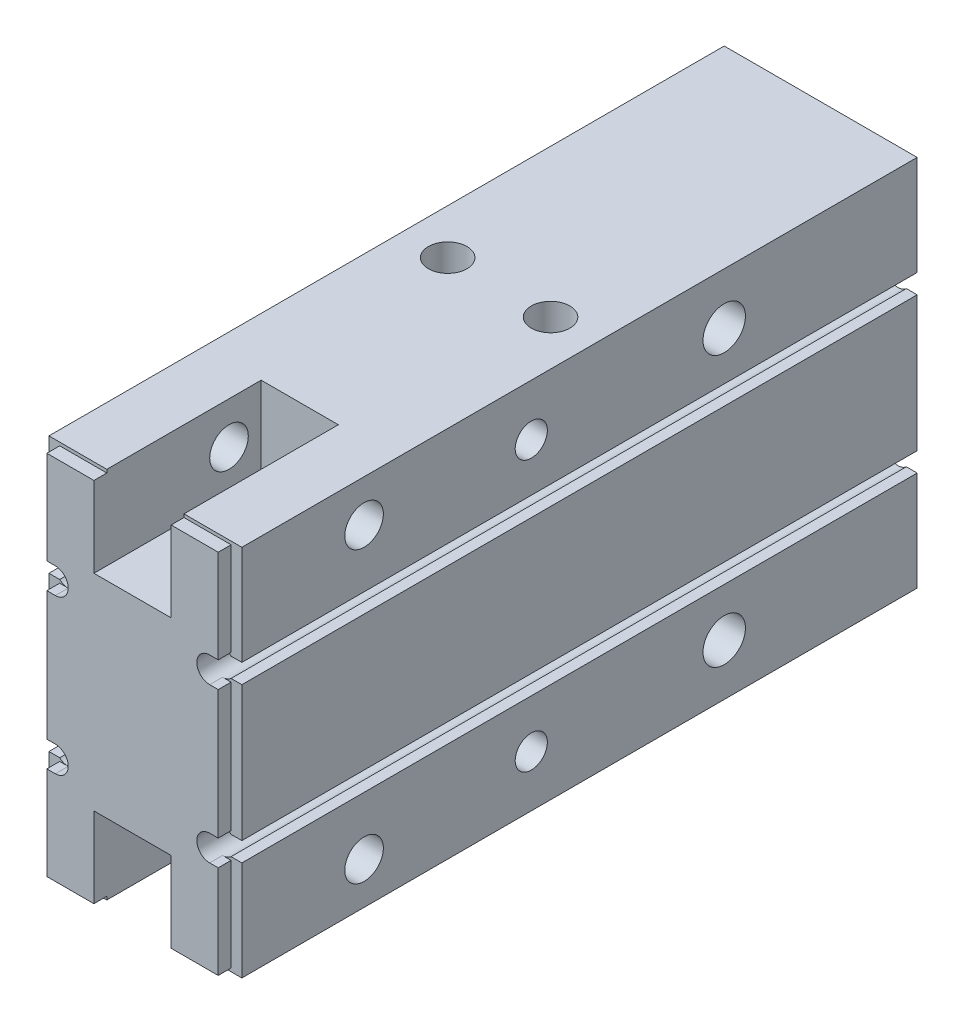
SolidWorks part; units mm, degrees
ref_plane "Top" through (0, 0, 0) normal (0, 0, 1) x (1, 0, 0)
ref_plane "Front" through (0, 0, 0) normal (0, 1, 0) x (1, 0, 0)
ref_plane "Right" through (0, 0, 0) normal (1, 0, 0) x (0, 0, -1)
sketch "Sketch1" plane through (0, 0, 0) normal (0, 0, 1) x (1, 0, 0)
  line L0 (-120, 0) -> (140, 0) construction
  line L1 (0, 110) -> (0, -100) construction
  line L2 (-15, 29) -> (15, 29)
  line L3 (15, 29) -> (15, 13.5)
  line L4 (-40, 12) -> (70, 12) construction
  line L5 (13.3229, 13.5) -> (15, 13.5)
  line L6 (13.3229, 10.5) -> (15, 10.5)
  line L7 (15, 10.5) -> (15, -10.5)
  line L8 (13.3229, -13.5) -> (15, -13.5)
  line L9 (13.3229, -10.5) -> (15, -10.5)
  line L10 (15, -29) -> (15, -13.5)
  line L11 (-15, -29) -> (15, -29)
  line L12 (-13.3229, -13.5) -> (-15, -13.5)
  line L13 (-13.3229, -10.5) -> (-15, -10.5)
  line L14 (-13.3229, 10.5) -> (-15, 10.5)
  line L15 (-13.3229, 13.5) -> (-15, 13.5)
  line L16 (-15, -29) -> (-15, -13.5)
  line L17 (-15, 10.5) -> (-15, -10.5)
  line L18 (-15, 29) -> (-15, 13.5)
  arc A0 (13.3229, 10.5) -> (13.3229, 13.5) centre (12, 12) cw
  arc A1 (13.3229, -10.5) -> (13.3229, -13.5) centre (12, -12) ccw
  arc A2 (-13.3229, -10.5) -> (-13.3229, -13.5) centre (-12, -12) cw
  arc A3 (-13.3229, 10.5) -> (-13.3229, 13.5) centre (-12, 12) ccw
  point P20 (15, 0)
  point P31 (0, -29)
  point P34 (0, 29)
  dimension "GROOVEDIAMETER" = 4
  dimension "WIDTH" = 30
  dimension "HEIGHT" = 58
  dimension "EDGETOGROOVE" = 3
  dimension "CENTERTOGROOVE" = 12
  dimension "ARCEDGES" = 3
extrude "Body" add sketch "Sketch1" along normal blind 105
sketch "Sketch4" plane through (15, 0, 0) normal (1, 0, 0) x (0, 0, -1)
  line L0 (0, 0) -> (-60, 0) construction
  circle A0 centre (-30, 21) radius 3.3
  circle A1 centre (-30, -21) radius 3.3
  dimension "THRUHOLEDIAMETER" = 6.6
  dimension "CENTERTOHOLE" = 21
  dimension "EDGETOHOLE" = 30
extrude "ThroughHoles" cut sketch "Sketch4" against normal through all
sketch "Sketch6" plane through (15, -52.9203, -22.0414) normal (1, 0, 0) x (0, 0, -1)
  line L0 (-10, 52.9203) -> (-90, 52.9203) construction
  point P0 (-57.0414, 64.9203)
  dimension "EDGETOHOLE" = 35
  dimension "CENTERTOHOLE" = 12
sketch "Sketch7" plane through (7.5, 12, 35) normal (0, 1, 0) x (0, 0, -1)
  line L0 (0, 0) -> (0, 6.9013)
  line L1 (0, 6.9013) -> (1.5, 6)
  line L2 (1.5, 6) -> (1.5, 0)
  line L4 (1.5, 0) -> (0, 0)
  line L6 (0, 6.9013) -> (-1.5, 6) construction
  line L7 (0, -4.2442) -> (0, 117.3081) construction
  dimension "Diameter" = 3
  dimension "Depth" = 6
  dimension "Drill Angle" = 118
hole_wizard "M3 x 0.5 #1(Size=10)" positions "Sketch6" profile "Sketch7" legacy
cosmetic thread "Cosmetic Thread1"
mirror "M3 x 0.5 #2(Size=10)" [suppressed] about plane through (0, 0, 0) normal (0, 1, 0)
mirror "M3 x 0.5 Other Side (Size-10)" [suppressed] about plane through (0, 0, 0) normal (1, 0, 0)
ref_plane "FingerPivotPlane" through (0, 0, 47.5) normal (0, 0, -1) x (-1, 0, 0)
sketch "Sketch10" plane through (15, 0, 0) normal (1, 0, 0) x (0, 0, -1)
  line L1 (0, 0) -> (-60, 0) construction
  circle A0 centre (-86, 22.5) radius 3
  circle A1 centre (-86, -22.5) radius 3
  dimension "PIVOTHOLEDIAMETER" = 6
  dimension "BETWEENPIVOTHOLES" = 45
  dimension "EDGETOPIVOTHOLES" = 86
extrude "FingerPivotHoles" cut sketch "Sketch10" against normal through all
sketch "Sketch13" plane through (-54.6295, -67.953, 0) normal (0, 0, -1) x (-1, 0, 0)
  line L0 (-54.6295, 67.953) -> (-54.6295, 41.1673) construction
  line L1 (-54.6295, 67.953) -> (-65.2953, 67.953) construction
  point P0 (-59.1295, 55.953)
  dimension "D1" = 12
  dimension "D2" = 4.5
sketch "Sketch14" plane through (4.5, -12, 0) normal (1, 0, 0) x (0, 1, 0)
  line L0 (0, 0) -> (0, 6.9013)
  line L1 (0, 6.9013) -> (1.5, 6)
  line L2 (1.5, 6) -> (1.5, 0)
  line L4 (1.5, 0) -> (0, 0)
  line L6 (0, 6.9013) -> (-1.5, 6) construction
  line L7 (0, -4.2442) -> (0, 117.3081) construction
  dimension "Diameter" = 3
  dimension "Depth" = 6
  dimension "Drill Angle" = 118
hole_wizard "M3 x 0.5 BackHole1(Size=10)" positions "Sketch13" profile "Sketch14" legacy
cosmetic thread "Cosmetic Thread4"
sketch "Sketch15" plane through (-57.0024, -57.4961, 0) normal (0, 0, -1) x (-1, 0, 0)
  line L0 (-57.0024, 57.4961) -> (-47.2287, 57.4961) construction
  line L1 (-57.0024, 57.4961) -> (-57.0024, 74.8688) construction
  point P0 (-52.5024, 69.4961)
  dimension "D1" = 4.5
  dimension "D2" = 12
sketch "Sketch16" plane through (-4.5, 12, 0) normal (1, 0, 0) x (0, 1, 0)
  line L0 (0, 0) -> (0, 7.8026)
  line L1 (0, 7.8026) -> (3, 6)
  line L2 (3, 6) -> (3, 0)
  line L4 (3, 0) -> (0, 0)
  line L6 (0, 7.8026) -> (-3, 6) construction
  line L7 (0, -4.2442) -> (0, 117.3081) construction
  dimension "Diameter" = 6
  dimension "Depth" = 6
  dimension "Drill Angle" = 118
hole_wizard "M3 x 0.5 BackHole2(Size=10)" positions "Sketch15" profile "Sketch16" legacy
cosmetic thread "Cosmetic Thread5"
sketch "Sketch17" plane through (0, 0, 0) normal (0, 0, -1) x (-1, 0, 0)
  line L0 (-2, -22.5) -> (-2, -23.5)
  line L1 (0, 0) -> (0, -20) construction
  line L2 (2, -22.5) -> (2, -23.5)
  line L3 (-1.6896, -23) -> (1.7545, -23) construction
  arc A0 (-2, -22.5) -> (2, -22.5) centre (0, -22.5) cw
  arc A1 (-2, -23.5) -> (2, -23.5) centre (0, -23.5) ccw
  point P11 (2, -23)
  point P13 (-2, -23)
  dimension "WIDTH" = 4
  dimension "CENTERTOPINHOLE" = 23
  dimension "ARCTOARC" = 5
extrude "PositioningPinHole" cut sketch "Sketch17" against normal blind 4
sketch "Sketch19" plane through (15, -50.4003, -22.2138) normal (1, 0, 0) x (0, 0, -1)
  line L0 (-22.2138, 50.4003) -> (-91.423, 50.4003) construction
  point P0 (-51.1745, 65.1278)
  dimension "D1" = 14.7275
  dimension "D2" = 28.9607
sketch "Sketch20" plane through (10, 15, 41) normal (0, 1, 0) x (0, 0, -1)
  line L0 (0, 0) -> (0, 9.8026)
  line L1 (0, 9.8026) -> (3, 8)
  line L2 (3, 8) -> (3, 0)
  line L4 (3, 0) -> (0, 0)
  line L6 (0, 9.8026) -> (-3, 8) construction
  line L7 (0, -4.2442) -> (0, 117.3081) construction
  dimension "Diameter" = 6
  dimension "Depth" = 8
  dimension "Drill Angle" = 118
hole_wizard "M4 x 0.7 #1(Size=16)" positions "Sketch19" profile "Sketch20" legacy
cosmetic thread "Cosmetic Thread6"
mirror "M4 x 0.7 #2(Size=16)" [suppressed] about plane through (0, 0, 0) normal (0, 1, 0)
sketch "Sketch21" plane through (-45.6216, -81.2682, 0) normal (0, 0, -1) x (-1, 0, 0)
  point P0 (-51.1745, 65.1278)
  dimension "D1" = 16.1404
  dimension "D2" = 5.5529
sketch "Sketch22" plane through (6, -15, 0) normal (1, 0, 0) x (0, 1, 0)
  line L0 (0, 0) -> (0, 9.8026)
  line L1 (0, 9.8026) -> (3, 8)
  line L2 (3, 8) -> (3, 0)
  line L4 (3, 0) -> (0, 0)
  line L6 (0, 9.8026) -> (-3, 8) construction
  line L7 (0, -4.2442) -> (0, 117.3081) construction
  dimension "Diameter" = 6
  dimension "Depth" = 8
  dimension "Drill Angle" = 118
mirror "M4 x 0.7 Other Side(Size=16)" [suppressed] about plane through (0, 0, 0) normal (1, 0, 0)
hole_wizard "M4 x 0.7 BackHole1(Size=16)" positions "Sketch21" profile "Sketch22" legacy
cosmetic thread "Cosmetic Thread7"
sketch "Sketch23" plane through (-57.3197, -49.0614, 0) normal (0, 0, -1) x (-1, 0, 0)
  point P0 (-51.1745, 65.1278)
  dimension "D1" = 6.1452
  dimension "D2" = 16.0664
sketch "Sketch24" plane through (-6, 15, 0) normal (1, 0, 0) x (0, 1, 0)
  line L0 (0, 0) -> (0, 9.8026)
  line L1 (0, 9.8026) -> (3, 8)
  line L2 (3, 8) -> (3, 0)
  line L4 (3, 0) -> (0, 0)
  line L6 (0, 9.8026) -> (-3, 8) construction
  line L7 (0, -4.2442) -> (0, 117.3081) construction
  dimension "Diameter" = 6
  dimension "Depth" = 8
  dimension "Drill Angle" = 118
hole_wizard "M4 x 0.7 BackHole2(Size=16)" positions "Sketch23" profile "Sketch24" legacy
cosmetic thread "Cosmetic Thread8"
sketch "Sketch26" plane through (15, -46.961, 3.7549) normal (1, 0, 0) x (0, 0, -1)
  point P0 (-51.1745, 65.1278)
  dimension "D1" = 18.1667
  dimension "D2" = 54.9295
sketch "Sketch27" plane through (13, 18, 50) normal (0, 1, 0) x (0, 0, -1)
  line L0 (0, 0) -> (0, 11.8026)
  line L1 (0, 11.8026) -> (3, 10)
  line L2 (3, 10) -> (3, 0)
  line L4 (3, 0) -> (0, 0)
  line L6 (0, 11.8026) -> (-3, 10) construction
  line L7 (0, -4.2442) -> (0, 117.3081) construction
  dimension "Diameter" = 6
  dimension "Depth" = 10
  dimension "Drill Angle" = 118
hole_wizard "M5 x 0.8 #1(Size=20)" positions "Sketch26" profile "Sketch27" legacy
cosmetic thread "Cosmetic Thread9"
mirror "M5 x 0.8 #2(Size=20)" [suppressed] about plane through (0, 0, 0) normal (0, 1, 0)
sketch "Sketch31" plane through (-41.9158, -85.0481, 0) normal (0, 0, -1) x (-1, 0, 0)
  point P0 (-51.1745, 65.1278)
  dimension "D1" = 19.9203
  dimension "D2" = 9.2587
sketch "Sketch32" plane through (8, -19, 0) normal (1, 0, 0) x (0, 1, 0)
  line L0 (0, 0) -> (0, 11.8026)
  line L1 (0, 11.8026) -> (3, 10)
  line L2 (3, 10) -> (3, 0)
  line L4 (3, 0) -> (0, 0)
  line L6 (0, 11.8026) -> (-3, 10) construction
  line L7 (0, -4.2442) -> (0, 117.3081) construction
  dimension "Diameter" = 6
  dimension "Depth" = 10
  dimension "Drill Angle" = 118
mirror "M5 x 0.8 Other Side(Size=20)" [suppressed] about plane through (0, 0, 0) normal (1, 0, 0)
hole_wizard "M5 x 0.8 BackHole1(Size=20)" positions "Sketch31" profile "Sketch32" legacy
cosmetic thread "Cosmetic Thread11"
sketch "Sketch28" plane through (-58.7499, -46.5168, 0) normal (0, 0, -1) x (-1, 0, 0)
  point P0 (-51.1745, 65.1278)
  dimension "D1" = 7.5753
  dimension "D2" = 18.611
sketch "Sketch29" plane through (-8, 19, 0) normal (1, 0, 0) x (0, 1, 0)
  line L0 (0, 0) -> (0, 9.8026)
  line L1 (0, 9.8026) -> (3, 8)
  line L2 (3, 8) -> (3, 0)
  line L4 (3, 0) -> (0, 0)
  line L6 (0, 9.8026) -> (-3, 8) construction
  line L7 (0, -4.2442) -> (0, 117.3081) construction
  dimension "Diameter" = 6
  dimension "Depth" = 8
  dimension "Drill Angle" = 118
hole_wizard "M5 x 0.8 BackHole2(Size=20)" positions "Sketch28" profile "Sketch29" legacy
cosmetic thread "Cosmetic Thread10"
sketch "Sketch34" plane through (15, -42.1788, 12.8) normal (1, 0, 0) x (0, 0, -1)
  point P0 (-47.2, 63.1788)
  dimension "D1" = 60
  dimension "D2" = 21
sketch "Sketch35" plane through (15, 21, 60) normal (0, 1, 0) x (0, 0, -1)
  line L0 (0, 0) -> (0, 13.5022)
  line L1 (0, 13.5022) -> (2.5, 12)
  line L2 (2.5, 12) -> (2.5, 0)
  line L4 (2.5, 0) -> (0, 0)
  line L6 (0, 13.5022) -> (-2.5, 12) construction
  line L7 (0, -4.2442) -> (0, 117.3081) construction
  dimension "Diameter" = 5
  dimension "Depth" = 12
  dimension "Drill Angle" = 118
hole_wizard "M6 x 1.0 #1(Size=25)" positions "Sketch34" profile "Sketch35" legacy
cosmetic thread "Cosmetic Thread12"
mirror "M6 x 1.0 #2(Size=25)" about plane through (0, 0, 0) normal (0, 1, 0) of "M6 x 1.0 #1(Size=25)"
sketch "Sketch36" plane through (-60.7376, -41.4426, 0) normal (0, 0, -1) x (-1, 0, 0)
  point P0 (-51.7376, 64.4426)
  dimension "D1" = 9
  dimension "D2" = 23
sketch "Sketch37" plane through (-9, 23, 0) normal (1, 0, 0) x (0, 1, 0)
  line L0 (0, 0) -> (0, 13.8026)
  line L1 (0, 13.8026) -> (3, 12)
  line L2 (3, 12) -> (3, 0)
  line L4 (3, 0) -> (0, 0)
  line L6 (0, 13.8026) -> (-3, 12) construction
  line L7 (0, -4.2442) -> (0, 117.3081) construction
  dimension "Diameter" = 6
  dimension "Depth" = 12
  dimension "Drill Angle" = 118
mirror "M6 x 1.0 Other Side(Size=25)" about plane through (0, 0, 0) normal (1, 0, 0) of "M6 x 1.0 #2(Size=25)", "M6 x 1.0 #1(Size=25)"
hole_wizard "M6 x 1.0 BackHole1(Size=25)" positions "Sketch36" profile "Sketch37" legacy
cosmetic thread "Cosmetic Thread13"
sketch "Sketch38" plane through (-41.9451, -86.5891, 0) normal (0, 0, -1) x (-1, 0, 0)
  point P0 (-50.9451, 63.5891)
  dimension "D1" = 23
  dimension "D2" = 9
sketch "Sketch39" plane through (9, -23, 0) normal (1, 0, 0) x (0, 1, 0)
  line L0 (0, 0) -> (0, 13.8026)
  line L1 (0, 13.8026) -> (3, 12)
  line L2 (3, 12) -> (3, 0)
  line L4 (3, 0) -> (0, 0)
  line L6 (0, 13.8026) -> (-3, 12) construction
  line L7 (0, -4.2442) -> (0, 117.3081) construction
  dimension "Diameter" = 6
  dimension "Depth" = 12
  dimension "Drill Angle" = 118
hole_wizard "M6 x 1.0 BackHole2(Size=25)" positions "Sketch38" profile "Sketch39" legacy
cosmetic thread "Cosmetic Thread14"
sketch "Sketch45" plane through (50.2848, -29, -56.2575) normal (0, -1, 0) x (1, 0, 0)
  line L0 (-50.2848, 56.2575) -> (-50.2848, 115.8439) construction
  line L1 (-50.2848, 60.2575) -> (-50.2848, 56.2575) construction
  point P0 (-57.2848, 64.2575)
  dimension "CENTERTOPORT" = 7
  dimension "EDGETOPORT" = 8
sketch "Sketch46" plane through (-7, -29, 8) normal (1, 0, 0) x (0, 0, -1)
  line L0 (0, 0) -> (0, 6.5022)
  line L1 (0, 6.5022) -> (2.5, 5)
  line L2 (2.5, 5) -> (2.5, 0)
  line L4 (2.5, 0) -> (0, 0)
  line L6 (0, 6.5022) -> (-2.5, 5) construction
  line L7 (0, -4.2442) -> (0, 117.3081) construction
  dimension "Diameter" = 5
  dimension "Depth" = 5
  dimension "Drill Angle" = 118
hole_wizard "M5 x 0.8 Port #1" positions "Sketch45" profile "Sketch46" legacy
cosmetic thread "Cosmetic Thread15"
sketch "Sketch47" plane through (54.7336, -29, -22.3356) normal (0, -1, 0) x (1, 0, 0)
  line L0 (-54.7336, 22.3356) -> (-54.7336, 82.3668) construction
  line L1 (-54.7336, 26.3356) -> (-54.7336, 22.3356) construction
  point P0 (-47.7336, 72.3356)
  dimension "PORTTOPORT" = 42
  dimension "CENTERTOPORT" = 7
sketch "Sketch48" plane through (7, -29, 50) normal (1, 0, 0) x (0, 0, -1)
  line L0 (0, 0) -> (0, 9.0022)
  line L1 (0, 9.0022) -> (2.5, 7.5)
  line L2 (2.5, 7.5) -> (2.5, 0)
  line L4 (2.5, 0) -> (0, 0)
  line L6 (0, 9.0022) -> (-2.5, 7.5) construction
  line L7 (0, -4.2442) -> (0, 117.3081) construction
  dimension "Diameter" = 5
  dimension "Depth" = 7.5
  dimension "Drill Angle" = 118
hole_wizard "M5 x 0.8 Port #2" positions "Sketch47" profile "Sketch48" legacy
cosmetic thread "Cosmetic Thread16"
sketch "Sketch49" plane through (0, 0, 105) normal (0, 0, 1) x (1, 0, 0)
  line L0 (12, 14) -> (13.3229, 14)
  line L1 (-13.3229, 28.5) -> (13.3229, 28.5)
  line L2 (0, 18.6333) -> (0, -17.5075) construction
  line L3 (-13.3229, -28.5) -> (13.3229, -28.5)
  line L4 (13.3229, 28.5) -> (13.3229, 14)
  line L5 (12, 10) -> (13.3229, 10)
  line L6 (12, -10) -> (13.3229, -10)
  line L7 (12, -14) -> (13.3229, -14)
  line L8 (13.3229, 10) -> (13.3229, -10)
  line L9 (13.3229, -14) -> (13.3229, -28.5)
  line L10 (15, 29) -> (-15, 29) construction
  line L11 (-10.0611, 0) -> (11.5055, 0) construction
  line L12 (-13.3229, -14) -> (-13.3229, -28.5)
  line L13 (-12, -14) -> (-13.3229, -14)
  line L14 (-12, -10) -> (-13.3229, -10)
  line L15 (-13.3229, 10) -> (-13.3229, -10)
  line L16 (-12, 10) -> (-13.3229, 10)
  line L17 (-12, 14) -> (-13.3229, 14)
  line L18 (-13.3229, 28.5) -> (-13.3229, 14)
  line L19 (-15, 29) -> (-15, 13.5) construction
  arc A1 (-13.3229, 10.5) -> (-13.3229, 13.5) centre (-12, 12) ccw construction
  arc A4 (12, 14) -> (12, 10) centre (12, 12) ccw
  arc A5 (-12, 10) -> (-12, 14) centre (-12, 12) ccw
  arc A6 (-12, -14) -> (-12, -10) centre (-12, -12) ccw
  arc A7 (12, -10) -> (12, -14) centre (12, -12) ccw
  arc A8 (-13.3229, -13.5) -> (-13.3229, -10.5) centre (-12, -12) ccw construction
  dimension "D1" = 1.6771
  dimension "EDGEOFFSET" = 0.5
extrude "EdgePlate" add sketch "Sketch49" along normal blind 2
sketch "Sketch50" plane through (-49.7922, 29, -17.8123) normal (0, 1, 0) x (-1, 0, 0)
  line L0 (-49.7922, 17.8123) -> (-49.7922, 78.1444) construction
  line L1 (-49.7922, 21.8123) -> (-49.7922, 17.8123) construction
  point P0 (-51.1745, 65.1278)
  dimension "D1" = 1.3823
  dimension "D2" = 47.3155
sketch "Sketch51" plane through (4.5, 15, 30) normal (1, 0, 0) x (0, 0, 1)
  line L0 (0, 0) -> (0, 5.8026)
  line L1 (0, 5.8026) -> (3, 4)
  line L2 (3, 4) -> (3, 0)
  line L4 (3, 0) -> (0, 0)
  line L6 (0, 5.8026) -> (-3, 4) construction
  line L7 (0, -4.2442) -> (0, 117.3081) construction
  dimension "Diameter" = 6
  dimension "Depth" = 4
  dimension "Drill Angle" = 118
hole_wizard "M3 x 0.5 TopHole1(Size=10)" positions "Sketch50" profile "Sketch51" legacy
cosmetic thread "Cosmetic Thread17"
mirror "M3 x 0.5 TopHole2(Size=10)" [suppressed] about plane through (0, 0, 0) normal (1, 0, 0)
sketch "Sketch52" plane through (-51.4486, 29, -11.5795) normal (0, 1, 0) x (-1, 0, 0)
  line L0 (-51.4486, 11.5795) -> (-51.4486, 84.9983) construction
  line L1 (-51.4486, 15.5795) -> (-51.4486, 11.5795) construction
  point P0 (-51.1745, 65.1278)
  dimension "D1" = 0.2741
  dimension "D2" = 53.5483
sketch "Sketch53" plane through (-6, 19, 33) normal (1, 0, 0) x (0, 0, 1)
  line L0 (0, 0) -> (0, 6.8026)
  line L1 (0, 6.8026) -> (3, 5)
  line L2 (3, 5) -> (3, 0)
  line L4 (3, 0) -> (0, 0)
  line L6 (0, 6.8026) -> (-3, 5) construction
  line L7 (0, -4.2442) -> (0, 117.3081) construction
  dimension "Diameter" = 6
  dimension "Depth" = 5
  dimension "Drill Angle" = 118
hole_wizard "M4 x 0.7 TopHole1(Size=16)" positions "Sketch52" profile "Sketch53" legacy
cosmetic thread "Cosmetic Thread18"
mirror "M4 x 0.7 TopHole2(Size=16)" [suppressed] about plane through (0, 0, 0) normal (1, 0, 0)
sketch "Sketch54" plane through (-57.1526, 29, -3.3396) normal (0, 1, 0) x (-1, 0, 0)
  point P0 (-51.1745, 65.1278)
  dimension "D1" = 5.978
  dimension "D2" = 61.7882
sketch "Sketch55" plane through (-7, 24, 42) normal (1, 0, 0) x (0, 0, 1)
  line L0 (0, 0) -> (0, 9.8026)
  line L1 (0, 9.8026) -> (3, 8)
  line L2 (3, 8) -> (3, 0)
  line L4 (3, 0) -> (0, 0)
  line L6 (0, 9.8026) -> (-3, 8) construction
  line L7 (0, -4.2442) -> (0, 117.3081) construction
  dimension "Diameter" = 6
  dimension "Depth" = 8
  dimension "Drill Angle" = 118
hole_wizard "M5 x 0.8 TopHole1(Size=20)" positions "Sketch54" profile "Sketch55" legacy
cosmetic thread "Cosmetic Thread19"
mirror "M5 x 0.8 TopHole2(Size=20)" [suppressed] about plane through (0, 0, 0) normal (1, 0, 0)
sketch "Sketch56" plane through (-59.6749, 29, 15.5733) normal (0, 1, 0) x (-1, 0, 0)
  point P0 (-51.6749, 34.4267)
  dimension "D1" = 8
  dimension "D2" = 50
sketch "Sketch57" plane through (-8, 29, 50) normal (1, 0, 0) x (0, 0, 1)
  line L0 (0, 0) -> (0, 11.8026)
  line L1 (0, 11.8026) -> (3, 10)
  line L2 (3, 10) -> (3, 0)
  line L4 (3, 0) -> (0, 0)
  line L6 (0, 11.8026) -> (-3, 10) construction
  line L7 (0, -4.2442) -> (0, 117.3081) construction
  dimension "Diameter" = 6
  dimension "Depth" = 10
  dimension "Drill Angle" = 118
hole_wizard "M6 x 1.0 TopHole1(Size=25)" positions "Sketch56" profile "Sketch57" legacy
cosmetic thread "Cosmetic Thread20"
mirror "M6 x 1.0 TopHole2(Size=25)" about plane through (0, 0, 0) normal (1, 0, 0) of "M6 x 1.0 TopHole1(Size=25)"
sketch "Sketch58" plane through (0, 0, 107) normal (0, 0, 1) x (1, 0, 0)
  line L0 (0, 0) -> (0, 16.7626) construction
  line L1 (-6, 29) -> (-6, 16)
  line L2 (-6, 16) -> (6, 16)
  line L3 (6, 16) -> (6, 29)
  line L4 (6, 29) -> (-6, 29)
  line L5 (15, 29) -> (-15, 29) construction
  dimension "CUTWIDTH" = 12
  dimension "CUTHEIGHT" = 13
extrude "FingerCutout1" cut sketch "Sketch58" against normal blind 26
ref_plane "TopPivotPlane" through (0, 22.5, 0) normal (0, 1, 0) x (-1, 0, 0)
ref_plane "BottomPivotPlane" through (0, -22.5, 0) normal (0, 1, 0) x (-1, 0, 0)
ref_plane "FingerClosingPlaneTop" through (0, 25.4721, 0.8895) normal (0, 0.9994, 0.0349) x (-1, 0, 0)
ref_plane "FingerClosingPlaneBottom" through (0, -25.4721, 0.8895) normal (0, 0.9994, -0.0349) x (-1, 0, 0)
mirror "FingerCutout2" about plane through (0, 0, 0) normal (0, 1, 0) of "FingerCutout1"
ref_plane "AutoSwitchRearFace" through (0, 0, -3) normal (0, 0, -1) x (-1, 0, 0)
sketch "Sketch59" plane through (-6, 0, 0) normal (1, 0, 0) x (0, 0, -1)
  line L0 (-81, 29) -> (-81, 16) construction
  line L1 (-81, -16) -> (-95, -16)
  line L2 (-81, -16) -> (-81, -2)
  line L3 (-81, -2) -> (-95, -2)
  line L4 (-95, -16) -> (-95, -2)
  line L5 (-81, 16) -> (-95, 16)
  line L6 (-81, 16) -> (-81, 2)
  line L7 (-81, 2) -> (-95, 2)
  line L8 (-95, 16) -> (-95, 2)
  line L9 (-81, 16) -> (-107, 16) construction
  line L10 (-81, -16) -> (-107, -16) construction
  dimension "D1" = 14
  dimension "D2" = 14
extrude "FingerGap" cut sketch "Sketch59" along normal up to surface (12 mm away) up to face at (6, 24.5, 97.6667)
sketch "Sketch60" plane through (0, 0, 0) normal (0, 0, -1) x (-1, 0, 0)
  circle A0 centre (0, 0) radius 13
  dimension "D1" = 26
extrude "Cut-Extrude1" cut sketch "Sketch60" against normal blind 1.5
